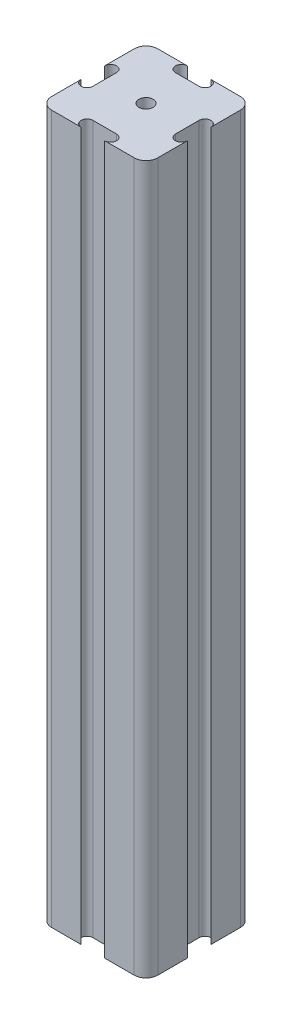
SolidWorks part; units mm, degrees
ref_plane "Front Plane" through (0, 0, 0) normal (0, 0, 1) x (1, 0, 0)
ref_plane "Top Plane" through (0, 0, 0) normal (0, 1, 0) x (1, 0, 0)
ref_plane "Right Plane" through (0, 0, 0) normal (1, 0, 0) x (0, 0, -1)
sketch "Esquisse4" plane through (0, 0, 0) normal (0, 1, 0) x (1, 0, 0)
  line L0 (-17.5, 22.5) -> (-5, 22.5)
  line L1 (22.5, 5) -> (22.5, 17.5)
  line L2 (0, 0) -> (22.5, 0) construction
  line L3 (5, 22.5) -> (17.5, 22.5)
  line L4 (0, 22.5) -> (0, 0) construction
  line L5 (-5, -17.5) -> (5, -17.5)
  line L6 (5, -22.5) -> (17.5, -22.5)
  line L7 (17.5, 5) -> (17.5, -5)
  line L8 (-5, -22.5) -> (-17.5, -22.5)
  line L10 (-5, 20) -> (5, 20) construction
  line L11 (0, 0) -> (0, -28.4326) construction
  line L12 (-5, 17.5) -> (5, 17.5)
  line L13 (17.5, 22.5) -> (17.5, -22.5) construction
  line L14 (-22.5, 17.5) -> (-22.5, 5)
  line L15 (-22.5, -5) -> (-22.5, -17.5)
  line L17 (-17.5, 5) -> (-17.5, -5)
  line L18 (0, 0) -> (-28.2169, 0) construction
  line L19 (22.5, -5) -> (22.5, -17.5)
  arc A0 (17.5, 22.5) -> (22.5, 17.5) centre (17.5, 17.5) cw
  arc A1 (17.5, -22.5) -> (22.5, -17.5) centre (17.5, -17.5) ccw
  arc A2 (-22.5, -17.5) -> (-17.5, -22.5) centre (-17.5, -17.5) ccw
  arc A3 (-17.5, 22.5) -> (-22.5, 17.5) centre (-17.5, 17.5) ccw
  arc A5 (-5, 22.5) -> (-5, 17.5) centre (-5, 20) ccw
  arc A6 (5, 17.5) -> (5, 22.5) centre (5, 20) ccw
  arc A7 (-5, -17.5) -> (-5, -22.5) centre (-5, -20) ccw
  arc A8 (5, -22.5) -> (5, -17.5) centre (5, -20) ccw
  arc A9 (-17.5, -5) -> (-22.5, -5) centre (-20, -5) cw
  arc A10 (22.5, -5) -> (17.5, -5) centre (20, -5) cw
  arc A11 (-17.5, 5) -> (-22.5, 5) centre (-20, 5) ccw
  arc A12 (22.5, 5) -> (17.5, 5) centre (20, 5) ccw
  point P8 (22.5, 22.5)
  point P13 (0, -17.5)
  point P20 (-22.5, 22.5)
  point P23 (0, 20)
  dimension "D4" = 5
  dimension "D6" = 5
  dimension "D7" = 5
  dimension "D8" = 5
  dimension "D20" = 10
  dimension "D24" = 12.5
  dimension "D2" = 22.5
  dimension "D3" = 45
  dimension "D5" = 10
  dimension "D10" = 10
  dimension "D11" = 12.5
  dimension "D12" = 22.5
  dimension "D13" = 5
  dimension "D14" = 17.5
  dimension "D15" = 12.5
  dimension "D16" = 45
  dimension "D17" = 2.5
  dimension "D18" = 5
  dimension "D19" = 45
  dimension "D21" = 5
  dimension "D22" = 17.5
  dimension "D23" = 10
  dimension "D25" = 5
extrude "Boss.-Extru.2" add sketch "Esquisse4" along normal blind 300 contours L15 A2 L8 A7 L5 A8 L6 A1 L19 A10 L7 A12 L1 A0 L3 A6 L12 A5 L0 A3 L14 A11 L17 A9
sketch "Esquisse5" plane through (0, 0, 0) normal (0, -1, 0) x (1, 0, 0)
  circle A0 centre (0, 0) radius 3
extrude "Enlèv. mat.-Extru.1" cut sketch "Esquisse5" against normal through all
